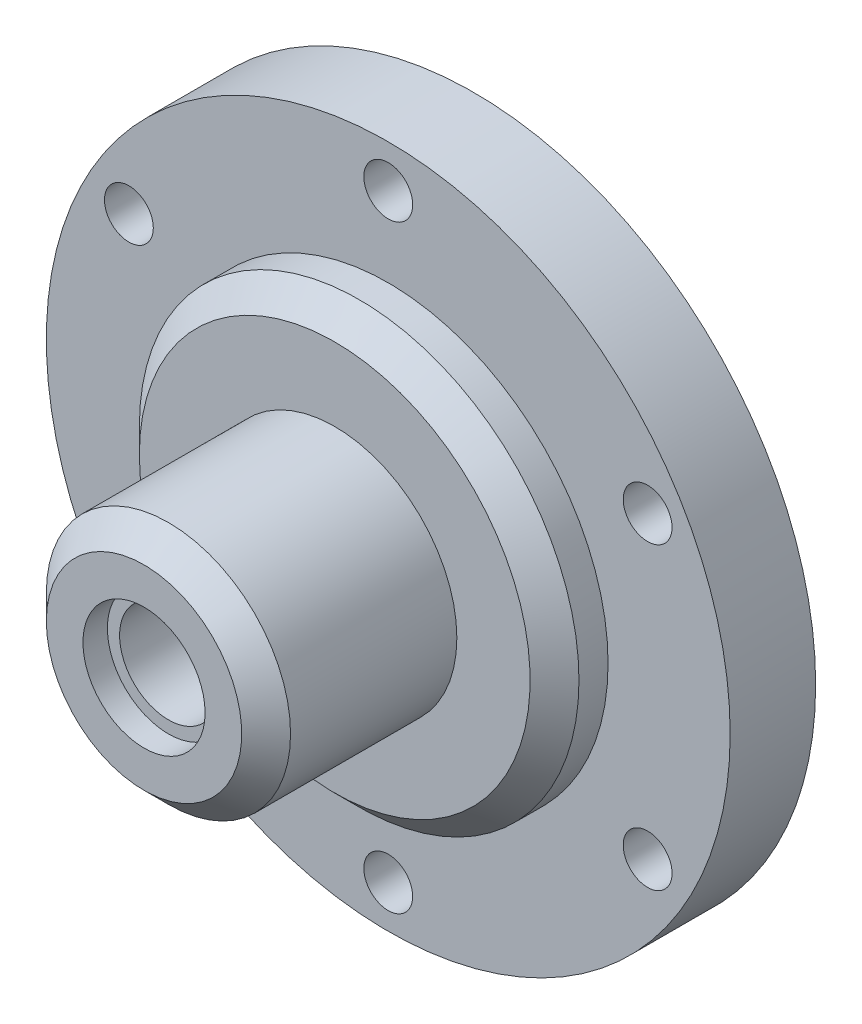
SolidWorks part; units mm, degrees
material "6061 Alloy"
ref_plane "Front Plane" through (0, 0, 0) normal (0, 0, 1) x (1, 0, 0)
ref_plane "Top Plane" through (0, 0, 0) normal (0, 1, 0) x (1, 0, 0)
ref_plane "Right Plane" through (0, 0, 0) normal (1, 0, 0) x (0, 0, -1)
sketch "Sketch1" plane through (0, 0, 0) normal (0, 0, 1) x (1, 0, 0)
  circle A0 centre (0, 0) radius 44
  dimension "D1" = 88
extrude "Tower Shaft" add sketch "Sketch1" along normal blind 20
sketch "Sketch2" plane through (0, 0, 0) normal (0, 0, 1) x (1, 0, 0)
  circle A0 centre (0, 0) radius 33.0914
  dimension "D1" = 66.1828
extrude "Main hole for propshaft" cut sketch "Sketch2" along normal blind 4500
sketch "Sketch3" plane through (0, 0, 0) normal (1, 0, 0) x (0, 0, -1)
  line L0 (-21.912, 50) -> (-21.912, 90)
  line L1 (-21.912, 90) -> (0, 90)
  line L2 (0, 170) -> (0, -170) construction
  line L3 (0, 20) -> (-100, 20)
  line L4 (0, 48.4) -> (0, -48.4) construction
  line L5 (11, 0) -> (-11, 0) construction
  line L6 (-100, 20) -> (-100, 50)
  line L7 (-100, 50) -> (-21.912, 50)
  line L8 (0, 50) -> (0, 20)
  line L9 (0, 90) -> (0, 50)
  dimension "D1" = 20
  dimension "D2" = 30
  dimension "D3" = 100
  dimension "D4" = 90
sketch "Sketch4" plane through (0, 0, 0) normal (0, 1, 0) x (1, 0, 0)
  line L0 (0, -4855.7148) -> (0, 309.4595)
  line L1 (0, -82.0875) -> (0, 82.0875) construction
revolve "Base Attachment Main body" add sketch "Sketch3" angle 360 about L0
chamfer "Base attachment chamfer" distance 10 2 edges at (50, 0, 100) (90, 0, 21.912)
sketch "Sketch5" plane through (0, 0, 0) normal (0, 0, 1) x (1, 0, 0)
  circle A0 centre (0, 0) radius 140
  circle A1 centre (0, 0) radius 70
  dimension "D1" = 280
  dimension "D2" = 140
extrude "Base Flange " add sketch "Sketch5" against normal blind 35
sketch "Sketch7" plane through (0, 0, 0) normal (0, 0, 1) x (1, 0, 0)
  line L0 (0, 0) -> (-122.625, 0) construction
  line L1 (154, 0) -> (-154, 0) construction
  circle A0 centre (0, 0) radius 140 construction
  circle A3 centre (0, 0) radius 105.25 construction
  circle A4 centre (0, 0) radius 122.625 construction
  circle A5 centre (0, 122.625) radius 10
  circle A6 centre (106.1964, 61.3125) radius 10
  circle A7 centre (106.1964, -61.3125) radius 10
  circle A8 centre (0, -122.625) radius 10
  circle A9 centre (-106.1964, -61.3125) radius 10
  circle A10 centre (-106.1964, 61.3125) radius 10
  point P23 (0, 0)
  dimension "D1" = 280
  dimension "D2" = 210.5
  dimension "D3" = 122.625
  dimension "D4" = 245.25
  dimension "D5" = 20
  dimension "D6" = 6
extrude "Base Flange Holes (M20)" cut sketch "Sketch7" against normal blind 35
sketch "Sketch8" plane through (0, 0, -35) normal (0, 0, -1) x (-1, 0, 0)
  line L0 (10, 75) -> (10, 67.9642)
  line L1 (0, 0) -> (10, 0) construction
  line L2 (0, 0) -> (0, 75) construction
  line L3 (-10, 75) -> (10, 75)
  line L4 (10, 0) -> (10, 75) construction
  line L5 (10, 67.9642) -> (-10, 67.9642)
  line L6 (-10, 75) -> (-10, 67.9642)
  point P8 (0, 67.9642)
  dimension "D1" = 10
  dimension "D2" = 75
extrude "Cut-Extrude1" cut sketch "Sketch8" against normal up to surface (35 mm away) up to face at (20, 0, 0)
scale "Scale1" scale about centroid uniform scaling yes scale factor 10
sketch "Sketch9" plane through (0, 0, 970.9835) normal (0, 0, 1) x (1, 0, 0)
  circle A0 centre (0, 0.9367) radius 200
  circle A1 centre (0, 0.9367) radius 250
  dimension "D1" = 50
extrude "Cut-Extrude2" cut sketch "Sketch9" against normal blind 100
